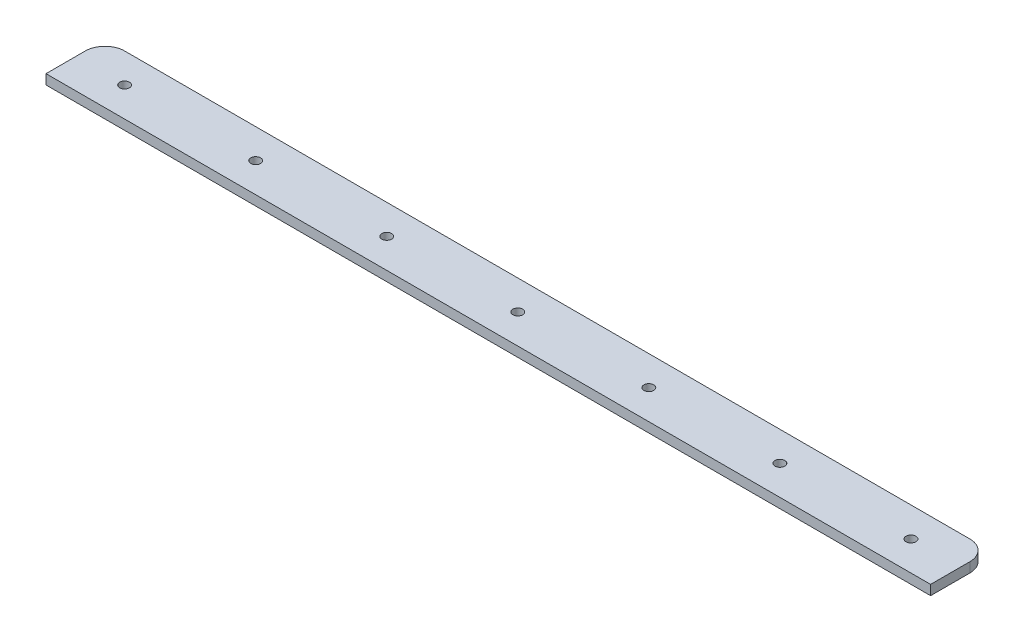
SolidWorks part; units mm, degrees
ref_plane "Front Plane" through (0, 0, 0) normal (0, 0, 1) x (1, 0, 0)
ref_plane "Top Plane" through (0, 0, 0) normal (0, 1, 0) x (1, 0, 0)
ref_plane "Right Plane" through (0, 0, 0) normal (1, 0, 0) x (0, 0, -1)
sketch "Sketch1" plane through (0, 0, 0) normal (0, 1, 0) x (1, 0, 0)
  line L1 (-750, -17.7839) -> (600, -17.7839)
  line L2 (-750, -17.7839) -> (-750, 42.2161)
  line L3 (-720, 72.2161) -> (570, 72.2161)
  line L4 (600, -17.7839) -> (600, 42.2161)
  line L5 (-750, -17.7839) -> (600, 72.2161) construction
  line L6 (-750, 72.2161) -> (600, -17.7839) construction
  arc A0 (570, 72.2161) -> (600, 42.2161) centre (570, 42.2161) cw
  arc A1 (-750, 42.2161) -> (-720, 72.2161) centre (-720, 42.2161) cw
  point P0 (0, 22.2161)
  dimension "D3" = 30
  dimension "D1" = 750
  dimension "D2" = 90
  dimension "D4" = 40
  dimension "D5" = 600
extrude "Boss-Extrude1" add sketch "Sketch1" along normal mid plane 15
sketch "Sketch2" plane through (0, -7.5, 0) normal (0, -1, 0) x (1, 0, 0)
  line L0 (-750, -42.2161) -> (-750, 17.7839) construction
  line L1 (-591.7035, 17.7839) -> (-591.7035, -72.2161) construction
  line L2 (-750, 17.7839) -> (600, 17.7839) construction
  line L3 (570, -72.2161) -> (-720, -72.2161) construction
  line L4 (-675, -27.2161) -> (-591.7035, -27.2161) construction
  circle A0 centre (-675, -27.2161) radius 7.5
  circle A1 centre (-475, -27.2161) radius 7.5
  circle A2 centre (-275, -27.2161) radius 7.5
  circle A3 centre (-75, -27.2161) radius 7.5
  circle A4 centre (125, -27.2161) radius 7.5
  circle A5 centre (325, -27.2161) radius 7.5
  circle A7 centre (525, -27.2161) radius 7.5 [skipped]
  circle A8 centre (525, -27.2161) radius 7.5
  point P14 (525, -27.2161)
  dimension "D1" = 15
  dimension "D6" = 15
  dimension "D3" = 75
  dimension "D4" = 200
  dimension "D2" = 7
extrude "Cut-Extrude1" cut sketch "Sketch2" against normal through all
